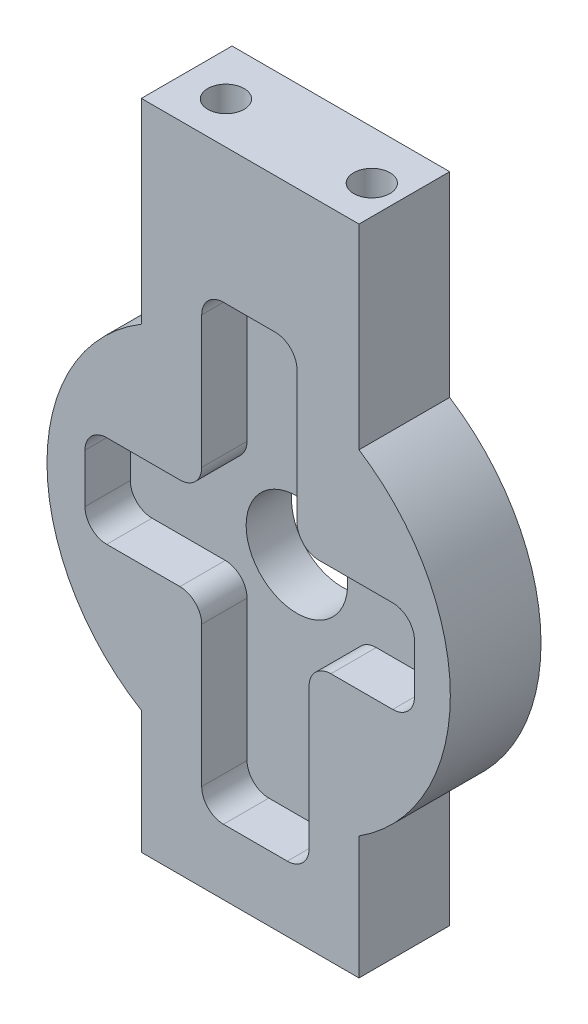
SolidWorks part; units mm, degrees
ref_plane "Front Plane" through (0, 0, 0) normal (0, 0, 1) x (1, 0, 0)
ref_plane "Top Plane" through (0, 0, 0) normal (0, 1, 0) x (1, 0, 0)
ref_plane "Right Plane" through (0, 0, 0) normal (1, 0, 0) x (0, 0, -1)
other "Graphic1"
ref_plane "Plane1" through (0, 0, 10) normal (0, 0, 1) x (1, 0, 0)
sketch "Sketch1" plane through (0, 0, 10) normal (0, 0, 1) x (1, 0, 0)
  line L0 (-246.9356, 240) -> (-246.9356, 200) construction
  line L1 (-257.9579, 223.6814) -> (-221.137, 223.6814) construction
  line L2 (-253, 244) -> (-241, 244)
  line L3 (-241, 244) -> (-241, 233.2195)
  line L4 (-241, 214.7805) -> (-241, 208)
  line L5 (-241, 208) -> (-253, 208)
  line L6 (-253, 208) -> (-253, 214.7805)
  line L7 (-253, 244) -> (-253, 233.2195)
  arc A0 (-241, 233.2195) -> (-241, 214.7805) centre (-246.9226, 224) cw
  arc A1 (-253, 233.2195) -> (-253, 214.7805) centre (-247.4317, 224) ccw
  circle A2 centre (-246.9226, 224) radius 2.8
  dimension "D1" = 12
  dimension "D2" = 36
extrude "Boss-Extrude1" add sketch "Sketch1" along normal blind 5
sketch "Sketch2" plane through (0, 0, 15) normal (0, 0, 1) x (1, 0, 0)
  line L0 (-249.6717, 236.5268) -> (-244.415, 236.5268)
  line L1 (-244.415, 236.5268) -> (-244.415, 226.8433)
  line L2 (-244.415, 226.8433) -> (-237.9409, 226.8433)
  line L3 (-237.9409, 226.8433) -> (-237.9409, 221.7526)
  line L4 (-237.9409, 221.7526) -> (-243.751, 221.7526)
  line L5 (-243.751, 221.7526) -> (-243.751, 211.6041)
  line L6 (-243.751, 211.6041) -> (-249.6717, 211.6041)
  line L7 (-249.6717, 211.6041) -> (-249.6717, 221.7526)
  line L8 (-249.6717, 221.7526) -> (-256.1089, 221.7526)
  line L9 (-256.1089, 221.7526) -> (-256.1089, 226.8433)
  line L10 (-256.1089, 226.8433) -> (-249.6717, 226.8433)
  line L11 (-249.6717, 226.8433) -> (-249.6717, 236.5268)
extrude "Cut-Extrude1" cut sketch "Sketch2" against normal blind 2.5
fillet "Fillet1" radius 1.2 12 edges at (-256.1089, 226.8433, 13.75) (-256.1089, 221.7526, 13.75) (-249.6717, 221.7526, 13.75) (-249.6717, 211.6041, 13.75) (-243.751, 211.6041, 13.75) (-243.751, 221.7526, 13.75) (-237.9409, 221.7526, 13.75) (-237.9409, 226.8433, 13.75) (-244.415, 226.8433, 13.75) (-249.6717, 226.8433, 13.75) (-249.6717, 236.5268, 13.75) (-244.415, 236.5268, 13.75)
sketch "Sketch3" plane through (0, 208, 0) normal (0, -1, 0) x (-1, 0, 0)
  line L0 (241, -15) -> (241, -10) construction
  line L1 (253, -10) -> (241, -10) construction
  circle A0 centre (250.9, -12.2) radius 1
  circle A1 centre (242.9, -12.2) radius 1
  dimension "D1" = 8
  dimension "D2" = 1.9
  dimension "D3" = 2.2
extrude "Cut-Extrude2" cut sketch "Sketch3" against normal blind 8
sketch "Sketch4" plane through (0, 244, 0) normal (0, 1, 0) x (1, 0, 0)
  circle A0 centre (-242.5988, -12.695) radius 1
  circle A1 centre (-250.6405, -12.695) radius 1
extrude "Cut-Extrude3" cut sketch "Sketch4" against normal blind 8
